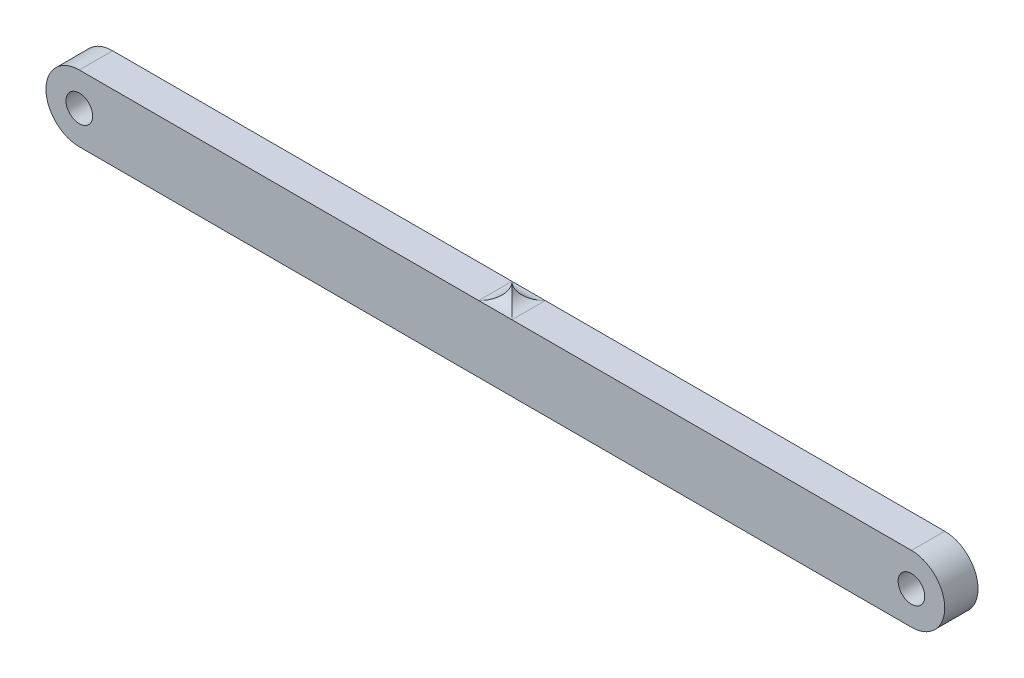
SolidWorks part; units mm, degrees
material "AISI 316 Stainless Steel Sheet (SS)"
ref_plane "Front Plane" through (0, 0, 0) normal (0, 0, 1) x (1, 0, 0)
ref_plane "Top Plane" through (0, 0, 0) normal (0, 1, 0) x (1, 0, 0)
ref_plane "Right Plane" through (0, 0, 0) normal (1, 0, 0) x (0, 0, -1)
sketch "Sketch1" plane through (0, 0, 0) normal (0, 0, 1) x (1, 0, 0)
  line L0 (-125, 0) -> (125, 0) construction
  line L1 (-125, 10) -> (125, 10)
  line L2 (-125, -10) -> (125, -10)
  arc A0 (-125, 10) -> (-125, -10) centre (-125, 0) ccw
  arc A1 (125, -10) -> (125, 10) centre (125, 0) ccw
  point P2 (0, 0)
  dimension "D1" = 20
  dimension "D2" = 250
extrude "Boss-Extrude1" add sketch "Sketch1" along normal mid plane 10
hole_wizard "Ø8.0mm Dowel Hole1" positions "Sketch2" profile "Sketch3" hole size "Ø8.0" standard "ISO" end condition through all
sketch "Sketch2" plane through (0, 0, 5) normal (0, 0, 1) x (1, 0, 0)
  point P0 (-125, 0)
  point P3 (125, 0)
sketch "Sketch3" plane through (-125, 0, 5) normal (1, 0, 0) x (0, -1, 0)
  line L0 (0, 0) -> (0, 10)
  line L1 (0, 10) -> (4, 10)
  line L2 (4, 10) -> (4, 0)
  line L5 (4, 0) -> (0, 0)
  line L11 (0, -6.35) -> (0, 107.95) construction
  dimension "Thru Hole Dia." = 8
  dimension "Thru Hole Depth" = 10
ref_point "Point1"
ref_point "Point2"
sketch "Sketch4" plane through (0, 0, 5) normal (0, 0, 1) x (1, 0, 0)
  line L0 (125, 10) -> (-125, 10) construction
  line L1 (-5, 10) -> (5, 10)
  arc A0 (-5, 10) -> (0, 15) centre (-5, 15) ccw
  arc A1 (0, 15) -> (5, 10) centre (5, 15) ccw
  dimension "D1" = 10
extrude "Boss-Extrude2" add sketch "Sketch4" against normal blind 10
sketch "Sketch5" plane through (0, 0, 0) normal (1, 0, 0) x (0, 0, -1)
  line L0 (5, 15) -> (-5, 15) construction
  line L1 (-5, 10) -> (-5, 20)
  line L2 (-5, 20) -> (5, 20)
  line L3 (5, 20) -> (5, 10)
  arc A0 (-5, 10) -> (0, 15) centre (-5, 15) ccw
  arc A1 (5, 10) -> (0, 15) centre (5, 15) cw
extrude "Cut-Extrude1" cut sketch "Sketch5" against normal through all both and the other way through all
ref_point "Point3"
sketch "Sketch6" plane through (0, 0, 5) normal (0, 0, 1) x (1, 0, 0)
  point P0 (-125, 0)
  point P1 (125, 0)
